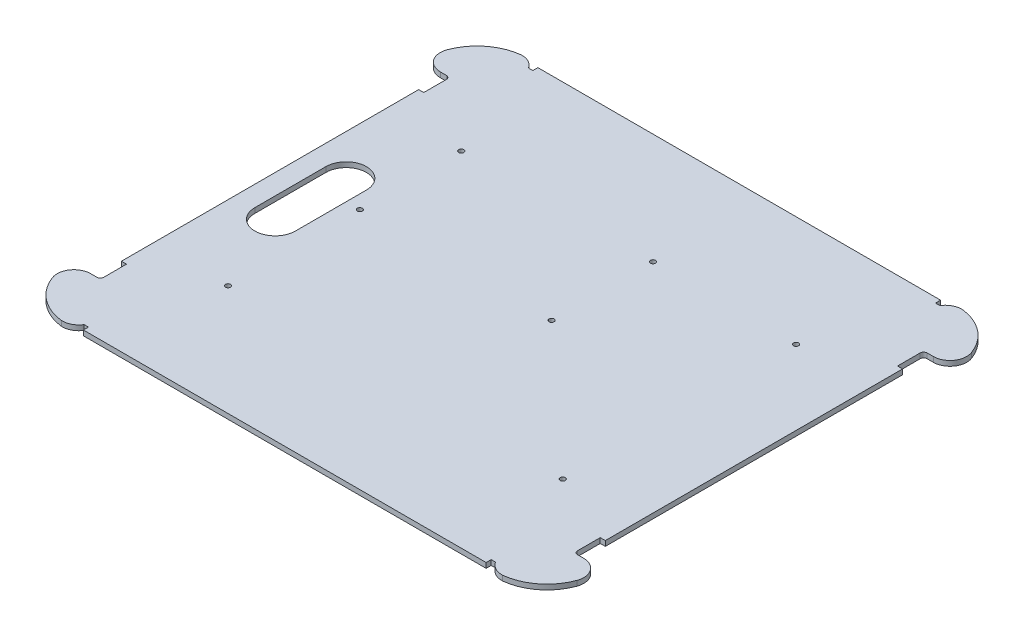
SolidWorks part; units mm, degrees
material "Glass"
ref_plane "Front Plane" through (0, 0, 0) normal (0, 0, 1) x (1, 0, 0)
ref_plane "Top Plane" through (0, 0, 0) normal (0, 1, 0) x (1, 0, 0)
ref_plane "Right Plane" through (0, 0, 0) normal (1, 0, 0) x (0, 0, -1)
sketch "Sketch1" plane through (0, 0, 0) normal (0, 1, 0) x (1, 0, 0)
  line L0 (-279.8278, 163.1917) -> (-273.8266, 163.1917)
  line L1 (-270.3266, 159.6917) -> (-270.3266, 137.4068)
  line L2 (-270.3266, 137.4068) -> (-275.3266, 137.4068)
  line L3 (-275.3266, 137.4068) -> (-275.3266, -155.6447)
  line L4 (-275.3266, -155.6447) -> (-270.3266, -155.6447)
  line L5 (-270.3266, -155.6447) -> (-270.3266, -177.9296)
  line L6 (-273.8266, -181.4296) -> (-279.8278, -181.4296)
  line L7 (-239.5978, -228.119) -> (-235.3266, -228.119)
  line L8 (-235.3266, -228.119) -> (-235.3266, -233.119)
  line L9 (-235.3266, -233.119) -> (161.6734, -233.119)
  line L10 (161.6734, -233.119) -> (161.6734, -228.119)
  line L11 (161.6734, -228.119) -> (165.9446, -228.119)
  line L12 (206.1745, -181.4296) -> (200.1734, -181.4296)
  line L13 (196.6734, -177.9296) -> (196.6734, -155.6447)
  line L14 (196.6734, -155.6447) -> (201.6734, -155.6447)
  line L15 (201.6734, -155.6447) -> (201.6734, 137.4068)
  line L16 (201.6734, 137.4068) -> (196.6734, 137.4068)
  line L17 (196.6734, 137.4068) -> (196.6734, 159.6917)
  line L18 (200.1734, 163.1917) -> (206.1745, 163.1917)
  line L19 (165.9446, 209.881) -> (161.6734, 209.881)
  line L20 (161.6734, 209.881) -> (161.6734, 214.881)
  line L21 (161.6734, 214.881) -> (-235.3266, 214.881)
  line L22 (-235.3266, 214.881) -> (-235.3266, 209.881)
  line L23 (-235.3266, 209.881) -> (-239.5978, 209.881)
  arc A0 (-239.5978, 209.881) -> (-254.3729, 217.5693) centre (-253.5605, 201.0893) ccw
  arc A1 (-254.3729, 217.5693) -> (-295.3283, 185.347) centre (-248.8266, 168.381) ccw
  arc A2 (-295.3283, 185.347) -> (-279.8278, 163.1917) centre (-279.8278, 179.6917) ccw
  arc A3 (-270.3266, 159.6917) -> (-273.8266, 163.1917) centre (-273.8266, 159.6917) ccw
  arc A4 (-273.8266, -181.4296) -> (-270.3266, -177.9296) centre (-273.8266, -177.9296) ccw
  arc A5 (-279.8278, -181.4296) -> (-295.3283, -203.5849) centre (-279.8278, -197.9296) ccw
  arc A6 (-295.3283, -203.5849) -> (-254.3729, -235.8073) centre (-248.8266, -186.619) ccw
  arc A7 (-254.3729, -235.8073) -> (-239.5978, -228.119) centre (-253.5605, -219.3273) ccw
  arc A8 (165.9446, -228.119) -> (180.7196, -235.8073) centre (179.9072, -219.3273) ccw
  arc A9 (180.7196, -235.8073) -> (221.675, -203.5849) centre (175.1734, -186.619) ccw
  arc A10 (221.675, -203.5849) -> (206.1745, -181.4296) centre (206.1745, -197.9296) ccw
  arc A11 (196.6734, -177.9296) -> (200.1734, -181.4296) centre (200.1734, -177.9296) ccw
  arc A12 (200.1734, 163.1917) -> (196.6734, 159.6917) centre (200.1734, 159.6917) ccw
  arc A13 (206.1745, 163.1917) -> (221.675, 185.347) centre (206.1745, 179.6917) ccw
  arc A14 (221.675, 185.347) -> (180.7196, 217.5693) centre (175.1734, 168.381) ccw
  arc A15 (180.7196, 217.5693) -> (165.9446, 209.881) centre (179.9072, 201.0893) ccw
extrude "Boss-Extrude1" add sketch "Sketch1" along normal blind 5
sketch "Sketch4" plane through (0, 0, 0) normal (0, -1, 0) x (1, 0, 0)
  line L0 (-36.8266, -214.881) -> (-36.8266, 233.119) construction
  line L1 (161.6734, -214.881) -> (-235.3266, -214.881) construction
  line L2 (-235.3266, 233.119) -> (161.6734, 233.119) construction
  line L3 (-36.8266, 9.119) -> (-275.3266, 9.119) construction
  line L4 (-275.3266, -137.4068) -> (-275.3266, 155.6447) construction
  circle A0 centre (-201.8266, 124.119) radius 2.5
  circle A1 centre (-201.8266, -105.881) radius 2.5
  circle A2 centre (128.1734, -105.881) radius 2.5
  circle A3 centre (128.1734, 124.119) radius 2.5
  dimension "D1" = 5
  dimension "D2" = 115
  dimension "D3" = 165
extrude "Cut-Extrude1" cut sketch "Sketch4" against normal blind 20
sketch "Sketch5" plane through (0, 5, 0) normal (0, 1, 0) x (1, 0, 0)
  line L0 (-235.3266, -44.119) -> (-235.3266, 25.881) construction
  line L1 (-255.3266, -44.119) -> (-255.3266, 25.881)
  line L2 (-215.3266, -44.119) -> (-215.3266, 25.881)
  line L3 (-275.3266, 137.4068) -> (-275.3266, -155.6447) construction
  line L4 (161.6734, 214.881) -> (-235.3266, 214.881) construction
  arc A0 (-255.3266, -44.119) -> (-215.3266, -44.119) centre (-235.3266, -44.119) ccw
  arc A1 (-215.3266, 25.881) -> (-255.3266, 25.881) centre (-235.3266, 25.881) ccw
  point P2 (-235.3266, -9.119)
  point P7 (0, 0)
  point P8 (-236.9298, 0)
  point P10 (-228.3364, 0)
  point P11 (0, 0)
  dimension "D1" = 40
  dimension "D2" = 70
  dimension "D3" = 40
  dimension "D4" = 224
extrude "Cut-Extrude2" cut sketch "Sketch5" against normal blind 10
sketch "Sketch8" plane through (0, 0, 0) normal (0, -1, 0) x (1, 0, 0)
  circle A18 centre (-201.8266, -105.881) radius 2.5
  circle A19 centre (-201.8266, -105.881) radius 2.5
  circle A21 centre (-201.8266, -5.881) radius 2.5
  circle A22 centre (-201.8266, -5.881) radius 2.5
  circle A24 centre (-12.8266, -5.881) radius 2.5
  circle A25 centre (-12.8266, -5.881) radius 2.5
  circle A74 centre (-12.8266, -105.881) radius 2.5
  dimension "D2" = 0
  dimension "D3" = 0
  dimension "D4" = 0
extrude "Cut-Extrude3" cut sketch "Sketch8" against normal blind 10
